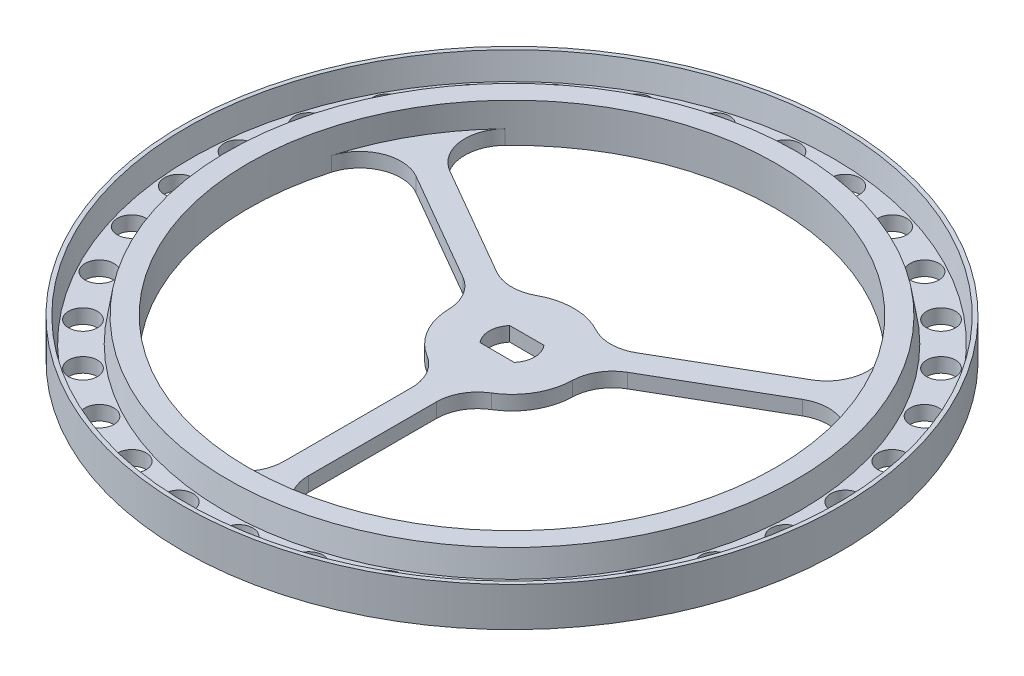
SolidWorks part; units mm, degrees
ref_plane "前视基准面" through (0, 0, 0) normal (0, 0, 1) x (1, 0, 0)
ref_plane "上视基准面" through (0, 0, 0) normal (0, 1, 0) x (1, 0, 0)
ref_plane "右视基准面" through (0, 0, 0) normal (1, 0, 0) x (0, 0, -1)
sketch "Sketch4" plane through (0, 0, 0) normal (0, 1, 0) x (1, 0, 0)
  line L0 (32, 0) -> (40, 0)
  line L1 (31.3851, 6.2429) -> (39.2314, 7.8036)
  line L2 (0, 0) -> (39.8074, 3.9207) construction
  line L8 (31.3851, 6.2429) -> (0, 0) construction
  line L9 (0, 0) -> (32, 0) construction
  arc A0 (40, 0) -> (39.2314, 7.8036) centre (0, 0) ccw
  arc A1 (31.3851, 6.2429) -> (32, 0) centre (0, 0) cw
  circle A2 centre (36.8218, 3.6266) radius 1.75
  point P9 (36.8218, 3.6266)
  dimension "D1" = 3
  dimension "D5" = 40
  dimension "D6" = 32
  dimension "D2" = 3.5
  dimension "D4" = 11.25
extrude "Boss-Extrude3" add sketch "Sketch4" along normal blind 1.75
pattern_circular "CirPattern1" count 32 over 360 about axis through (0, 0, 0) along (0, 1, 0) of "Boss-Extrude3"
sketch "Sketch5" plane through (0, 0, 0) normal (0, -1, 0) x (1, 0, 0)
  line L0 (2.0791, 1.8) -> (-2.0791, 1.8)
  line L1 (2.0791, -1.8) -> (-2.0791, -1.8)
  circle A0 centre (0, 0) radius 7.5
  circle A1 centre (0, 0) radius 2.75 construction
  arc A2 (-2.0791, 1.8) -> (-2.0791, -1.8) centre (0, 0) ccw
  arc A3 (2.0791, 1.8) -> (2.0791, -1.8) centre (0, 0) cw
  dimension "D1" = 15
  dimension "D2" = 1.8
  dimension "D3" = 5.5
extrude "Boss-Extrude4" add sketch "Sketch5" against normal up to surface (1.75 mm away) separate body up to face at (0, 1.75, -32)
sketch "Sketch7" plane through (0, 0, 0) normal (0, -1, 0) x (1, 0, 0)
  line L0 (0, 6.8) -> (0, 32) construction
  line L2 (-1.5, 6.8) -> (-1.5, 32)
  line L3 (-1.5, 6.8) -> (1.5, 6.8)
  line L4 (-1.5, 32) -> (1.5, 32)
  line L5 (1.5, 6.8) -> (1.5, 32)
  line L6 (-1.5, 6.8) -> (1.5, 32) construction
  line L7 (-1.5, 32) -> (1.5, 6.8) construction
  line L8 (2.0791, 1.8) -> (-2.0791, 1.8) construction
  circle A0 centre (0, 0) radius 32 construction
  point P8 (0, 19.4)
  dimension "D1" = 3
  dimension "D2" = 5
extrude "Boss-Extrude5" add sketch "Sketch7" against normal up to surface (1.75 mm away) up to face at (0, 1.75, -32)
fillet "Fillet1" radius 5 4 edges at (1.5, 0.875, 7.3485) (-1.5, 0.875, 7.3485) (1.5, 0.875, 31.9648) (-1.5, 0.875, 31.9648)
pattern_circular "CirPattern2" count 3 over 360 about axis through (0, 0, 0) along (0, 1, 0) of "Boss-Extrude5", "Fillet1"
sketch "Sketch8" plane through (0, 0, 0) normal (0, 0, 1) x (1, 0, 0)
  line L0 (-40, 1.75) -> (-40, 4.75)
  line L1 (-40, 4.75) -> (-39.5, 4.75)
  line L2 (-39, 1.75) -> (-40, 1.75)
  line L3 (-32, 1.75) -> (-32, 4.75)
  line L4 (-39.5, 4.75) -> (-39, 1.75)
  line L5 (-35, 1.75) -> (-32, 1.75)
  line L6 (-32, 4.75) -> (-34.5, 4.75)
  line L7 (-34.5, 4.75) -> (-35, 1.75)
  line L8 (0, 0) -> (0, 1.75) construction
  line L9 (40, 1.75) -> (-40, 1.75) construction
  dimension "D1" = 4
  dimension "D2" = 35
  dimension "D3" = 3
  dimension "D4" = 0.5
revolve "Revolve1" add sketch "Sketch8" angle 360 about L8
